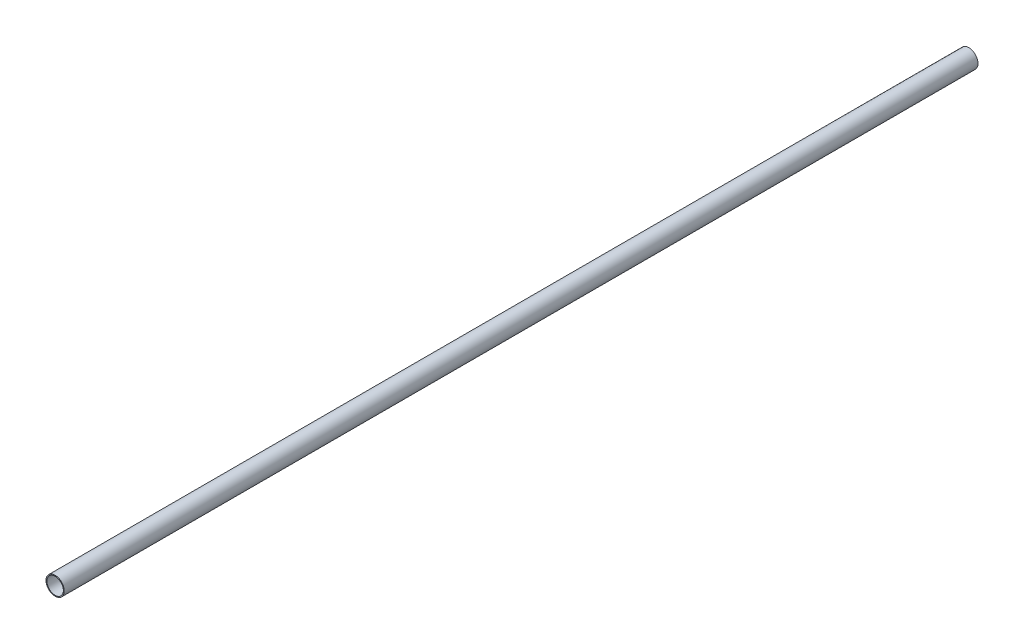
SolidWorks part; units mm, degrees
ref_plane "Спереди" through (0, 0, 0) normal (0, 0, 1) x (1, 0, 0)
ref_plane "Сверху" through (0, 0, 0) normal (0, 1, 0) x (1, 0, 0)
ref_plane "Справа" through (0, 0, 0) normal (1, 0, 0) x (0, 0, -1)
sketch "Эскиз1" plane through (0, 0, 0) normal (0, 0, 1) x (1, 0, 0)
  circle A0 centre (0, 0) radius 10
  circle A1 centre (0, 0) radius 9
  dimension "D1" = 20
  dimension "D2" = 18
extrude "Бобышка-Вытянуть1" add sketch "Эскиз1" along normal blind 1000
